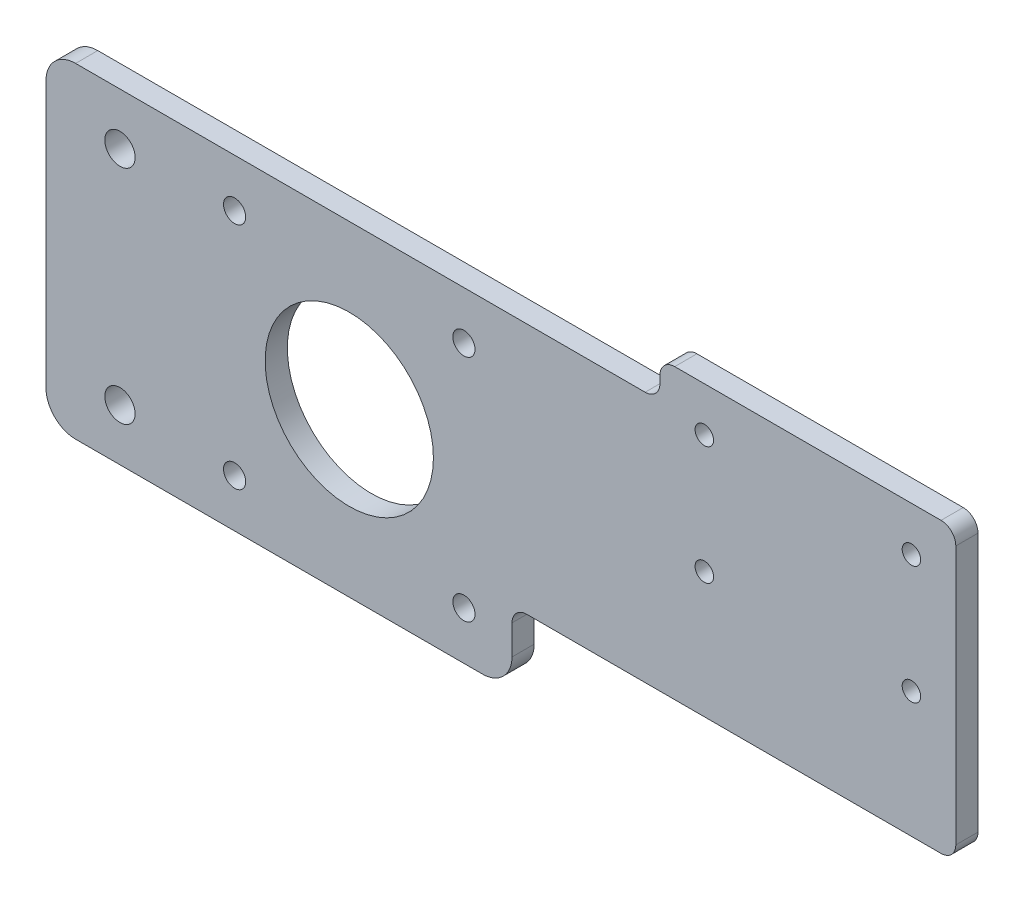
SolidWorks part; units mm, degrees
ref_plane "Front Plane" through (0, 0, 0) normal (0, 0, 1) x (1, 0, 0)
ref_plane "Top Plane" through (0, 0, 0) normal (0, 1, 0) x (1, 0, 0)
ref_plane "Right Plane" through (0, 0, 0) normal (1, 0, 0) x (0, 0, -1)
sketch "Sketch1" plane through (0, 0, 0) normal (0, 0, 1) x (1, 0, 0)
  line L1 (-31.5, 22) -> (31.5, 22)
  line L2 (-31.5, 22) -> (-31.5, -22)
  line L3 (-31.5, -22) -> (31.5, -22)
  line L4 (31.5, 22) -> (31.5, -22)
  line L5 (-31.5, 22) -> (31.5, -22) construction
  line L6 (-31.5, -22) -> (31.5, 22) construction
  point P0 (0, 0)
  dimension "D1" = 44
  dimension "D2" = 63
extrude "Boss-Extrude1" add sketch "Sketch1" along normal mid plane 3
sketch "Sketch3" plane through (0, 0, 1.5) normal (0, 0, 1) x (1, 0, 0)
  line L0 (31.5, -12) -> (91.5, -12)
  line L1 (31.5, -22) -> (31.5, 22) construction
  line L2 (91.5, -12) -> (91.5, 27)
  line L3 (91.5, 27) -> (51.5, 27)
  line L4 (51.5, 27) -> (51.5, 22)
  line L5 (51.5, 22) -> (31.5, 22)
  line L6 (31.5, 22) -> (31.5, -12)
  line L7 (-31.5, -22) -> (31.5, -22) construction
  dimension "D1" = 60
  dimension "D2" = 10
  dimension "D3" = 20
  dimension "D4" = 5
extrude "Boss-Extrude2" add sketch "Sketch3" against normal up to surface (3 mm away) up to face at (0, 0, -1.5)
sketch "Sketch2" plane through (0, 0, 1.5) normal (0, 0, 1) x (1, 0, 0)
  line L0 (0, 0) -> (9.5, 0) construction
  line L1 (31.5, -22) -> (31.5, -12) construction
  line L2 (0, 0) -> (-21.5, 0) construction
  line L3 (-6, 15.5) -> (25, 15.5) construction
  line L4 (-6, 15.5) -> (-6, -15.5) construction
  line L5 (-6, -15.5) -> (25, -15.5) construction
  line L6 (25, 15.5) -> (25, -15.5) construction
  line L7 (-6, 15.5) -> (25, -15.5) construction
  line L8 (-6, -15.5) -> (25, 15.5) construction
  line L9 (-21.5, 15) -> (-21.5, -15) construction
  line L10 (-31.5, 22) -> (-31.5, -22) construction
  circle A0 centre (9.5, 0) radius 11.375
  circle A1 centre (-6, 15.5) radius 1.5
  circle A2 centre (25, 15.5) radius 1.5
  circle A3 centre (25, -15.5) radius 1.5
  circle A4 centre (-6, -15.5) radius 1.5
  circle A5 centre (-21.5, 15) radius 2.05
  circle A6 centre (-21.5, -15) radius 2.05
  dimension "D1" = 22.75
  dimension "D3" = 3
  dimension "D5" = 4.1
  dimension "D7" = 10
  dimension "D2" = 22
  dimension "D4" = 31
  dimension "D6" = 30
extrude "Cut-Extrude1" cut sketch "Sketch2" against normal through all
fillet "Fillet1" radius 4 3 edges at (31.5, -22, 0) (-31.5, -22, 0) (-31.5, 22, 0)
hole_wizard "Tap Drill for M3x0.5 Tap1" positions "Sketch4" profile "Sketch5" hole size "M3x0.5" standard "ANSI Metric"
sketch "Sketch4" plane through (0, 0, 1.5) normal (0, 0, 1) x (1, 0, 0)
  line L0 (91.5, -12) -> (91.5, 27) construction
  line L1 (91.5, 27) -> (51.5, 27) construction
  point P0 (57.5, 21)
  point P2 (85.5, 21)
  point P4 (85.5, 5)
  point P6 (57.5, 5)
  point P7 (0, 0)
  point P8 (0, 0)
  point P9 (0, 0)
  dimension "D1" = 28
  dimension "D2" = 16
  dimension "D3" = 6
  dimension "D4" = 6
sketch "Sketch5" plane through (57.5, 21, 1.5) normal (1, 0, 0) x (0, -1, 0)
  line L0 (0, 0) -> (0, 4.7511)
  line L1 (0, 4.7511) -> (1.25, 4)
  line L2 (1.25, 4) -> (1.25, 0)
  line L5 (1.25, 0) -> (0, 0)
  line L10 (0, 4.7511) -> (-1.25, 4) construction
  line L11 (0, -6.35) -> (0, 107.95) construction
  dimension "Hole Dia." = 2.5
  dimension "Hole Depth" = 4
  dimension "Drill Angle" = 118
fillet "Fillet2" radius 2 5 edges at (91.5, 27, 0) (51.5, 27, 0) (51.5, 22, 0) (91.5, -12, 0) (31.5, -12, 0)
